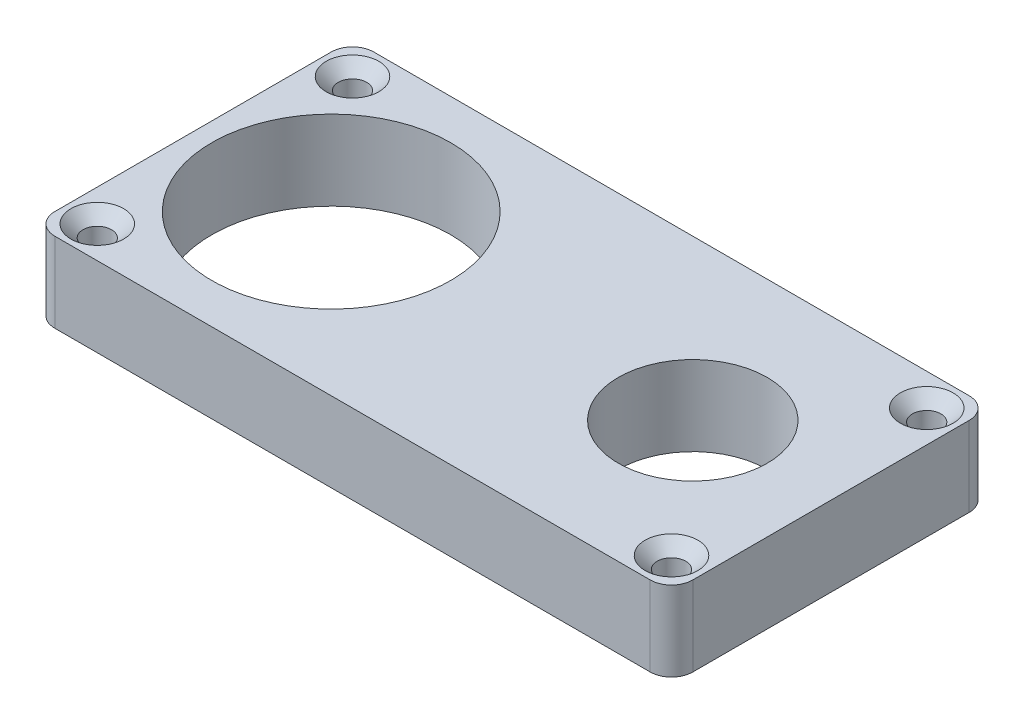
SolidWorks part; units mm, degrees
ref_plane "Front Plane" through (0, 0, 0) normal (0, 0, 1) x (1, 0, 0)
ref_plane "Top Plane" through (0, 0, 0) normal (0, 1, 0) x (1, 0, 0)
ref_plane "Right Plane" through (0, 0, 0) normal (1, 0, 0) x (0, 0, -1)
ref_plane "Plane1" through (0, 0, 0) normal (0, -1, 0) x (1, 0, 0)
sketch "Sketch1" plane through (0, 0, 0) normal (0, -1, 0) x (1, 0, 0)
  line L0 (-35.56, -19.05) -> (35.56, -19.05)
  line L1 (38.1, -16.51) -> (38.1, 16.51)
  line L2 (35.56, 19.05) -> (-35.56, 19.05)
  line L3 (-38.1, 16.51) -> (-38.1, -16.51)
  line L4 (0, 0) -> (0, 12.2265) construction
  circle A10 centre (21.59, 0) radius 8.89
  arc A13 (35.56, -19.05) -> (38.1, -16.51) centre (35.56, -16.51) ccw
  arc A14 (38.1, 16.51) -> (35.56, 19.05) centre (35.56, 16.51) ccw
  arc A15 (-35.56, 19.05) -> (-38.1, 16.51) centre (-35.56, 16.51) ccw
  arc A16 (-38.1, -16.51) -> (-35.56, -19.05) centre (-35.56, -16.51) ccw
  circle A17 centre (-21.59, 0) radius 14.265
  dimension "D1" = 28.53
  dimension "D5" = 2.54
  dimension "D8" = 17.78
  dimension "D2" = 43.18
  dimension "D3" = 76.2
  dimension "D4" = 38.1
  dimension "D6" = 19.05
  dimension "D7" = 38.1
extrude "Boss-Extrude1" add sketch "Sketch1" against normal blind 9.525
ref_plane "Plane2" through (0, 0, 0) normal (0, 0, 1) x (1, 0, 0)
hole_wizard "CSK for M3 Flat Head Machine Screw1" positions "Sketch3" profile "Sketch4" countersink size "M3" standard "ANSI Metric"
sketch "Sketch3" plane through (0, 9.525, 0) normal (0, 1, 0) x (1, 0, 0)
  line L0 (0, 0) -> (10.5209, 0) construction
  line L2 (0, 0) -> (0, 8.584) construction
  line L4 (-35.56, 19.05) -> (35.56, 19.05) construction
  line L5 (-38.1, -16.51) -> (-38.1, 16.51) construction
  point P0 (-34.29, 15.24)
  point P2 (-34.29, -15.24)
  point P4 (34.29, -15.24)
  point P6 (34.29, 15.24)
  dimension "D1" = 3.81
  dimension "D2" = 3.81
sketch "Sketch4" plane through (-34.29, 9.525, -15.24) normal (1, 0, 0) x (0, 0, 1)
  line L0 (0, 0) -> (0, 11.0214)
  line L1 (0, 11.0214) -> (1.7, 10)
  line L2 (1.7, 10) -> (1.7, 1.45)
  line L3 (1.7, 1.45) -> (3.15, 0)
  line L5 (3.15, 0) -> (0, 0)
  line L6 (-1.7, 1.45) -> (-3.15, 0) construction
  line L10 (0, 11.0214) -> (-1.7, 10) construction
  line L11 (0, -6.35) -> (0, 107.95) construction
  dimension "Hole Dia." = 3.4
  dimension "Hole Depth" = 10
  dimension "Near C'Sink Dia." = 6.3
  dimension "Near C'Sink Angle" = 90
  dimension "Drill Angle" = 118
hole_wizard "M3x0.5 Tapped Hole1" positions "Sketch6" profile "Sketch7" tap size "M3x0.5" standard "ANSI Metric"
sketch "Sketch6" plane through (0, 6.35, 0) normal (0, 1, 0) x (1, 0, 0)
  point P0 (-34.29, 15.24)
  point P3 (34.29, 15.24)
  point P6 (34.29, -15.24)
  point P8 (-34.29, -15.24)
sketch "Sketch7" plane through (-34.29, 6.35, -15.24) normal (1, 0, 0) x (0, 0, 1)
  line L0 (0, 0) -> (0, 6.35)
  line L1 (0, 6.35) -> (1.25, 6.35)
  line L2 (1.25, 6.35) -> (1.25, 0)
  line L5 (1.25, 0) -> (0, 0)
  line L11 (0, -6.35) -> (0, 107.95) construction
  dimension "Thread Major Dia." = 2.5
  dimension "Thru Tap Drill Depth" = 6.35
